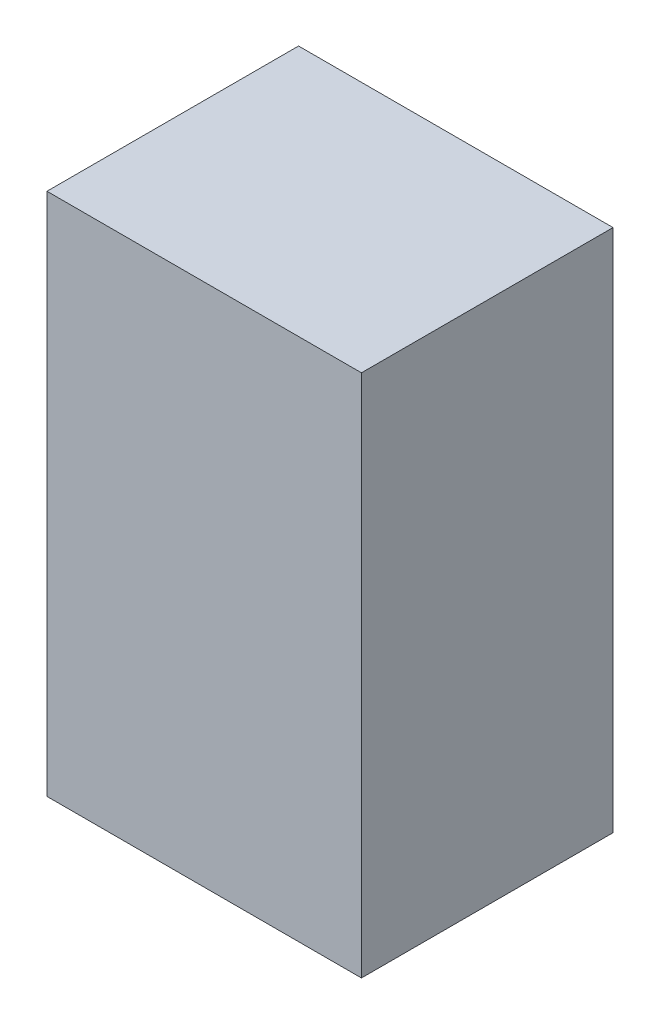
SolidWorks part; units mm, degrees
ref_plane "前视基准面" through (0, 0, 0) normal (0, 0, 1) x (1, 0, 0)
ref_plane "上视基准面" through (0, 0, 0) normal (0, 1, 0) x (1, 0, 0)
ref_plane "右视基准面" through (0, 0, 0) normal (1, 0, 0) x (0, 0, -1)
other "Configuration Table"
sketch "草图1" plane through (0, 0, 0) normal (0, 0, 1) x (1, 0, 0)
  line L1 (0, 0) -> (6, 0)
  line L2 (0, 0) -> (0, 10)
  line L3 (0, 10) -> (6, 10)
  line L4 (6, 0) -> (6, 10)
  dimension "D1" = 10
  dimension "D2" = 6
extrude "凸台-拉伸1" add sketch "草图1" along normal blind 4.8
